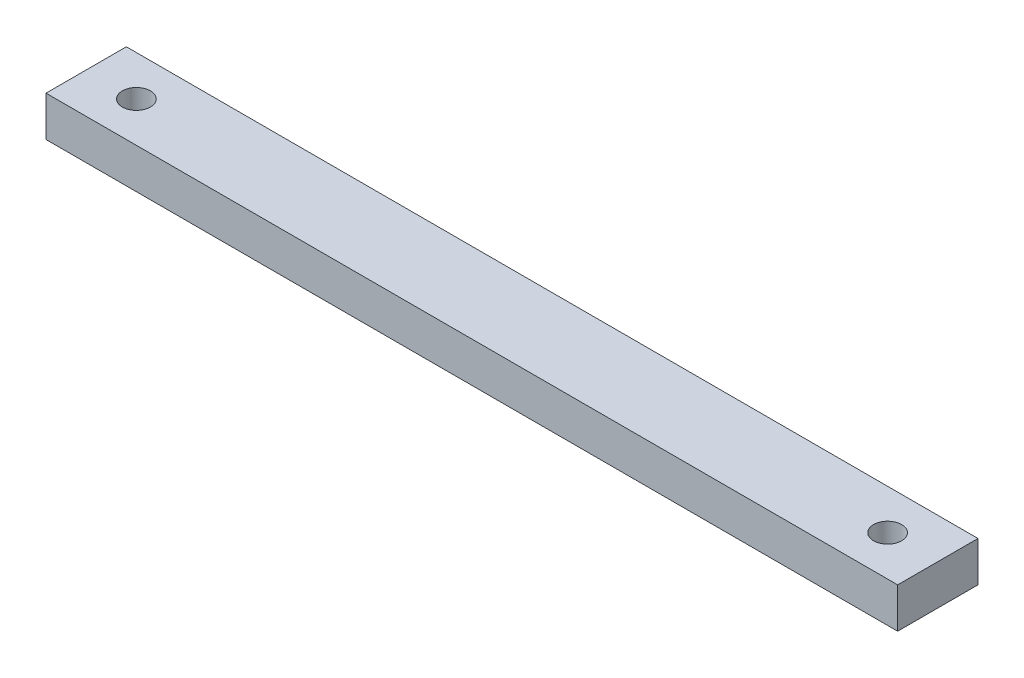
SolidWorks part; units mm, degrees
ref_plane "Front" through (0, 0, 0) normal (0, 0, 1) x (1, 0, 0)
ref_plane "Top" through (0, 0, 0) normal (0, 1, 0) x (1, 0, 0)
ref_plane "Right" through (0, 0, 0) normal (1, 0, 0) x (0, 0, -1)
sketch "Эскиз1" plane through (0, 0, 0) normal (0, 1, 0) x (1, 0, 0)
  line L0 (0, 0) -> (0, -10.7482) construction
  line L1 (-10.6, 1) -> (10.6, 1)
  line L2 (-10.6, 1) -> (-10.6, -1)
  line L3 (-10.6, -1) -> (10.6, -1)
  line L4 (10.6, 1) -> (10.6, -1)
  line L5 (-10.6, 1) -> (10.6, -1) construction
  line L6 (-10.6, -1) -> (10.6, 1) construction
  circle A0 centre (-9.35, 0) radius 0.35
  circle A1 centre (9.35, 0) radius 0.35
  point P0 (0, 0)
  dimension "D3" = 0.7
  dimension "D1" = 2
  dimension "D2" = 21.2
  dimension "D4" = 9.35
  dimension "D5" = 1
extrude "Бобышка-Вытянуть1" add sketch "Эскиз1" along normal blind 1
